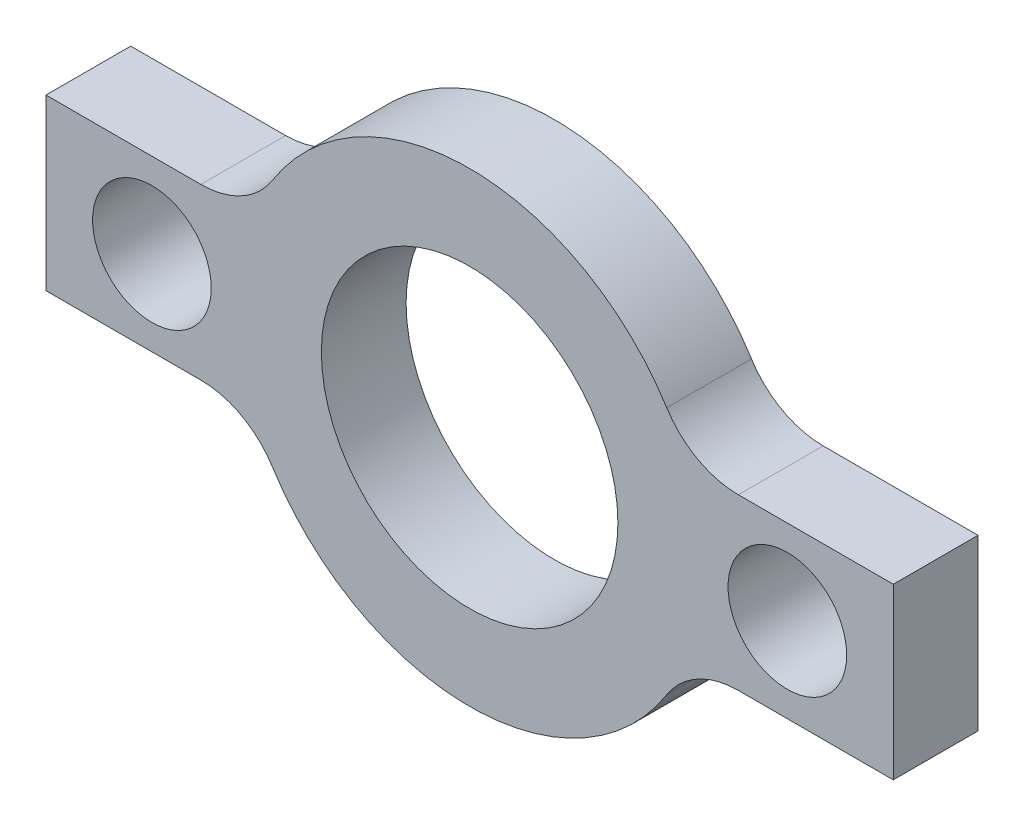
SolidWorks part; units mm, degrees
material "尼龙 101"
ref_plane "前视基准面" through (0, 0, 0) normal (0, 0, 1) x (1, 0, 0)
ref_plane "上视基准面" through (0, 0, 0) normal (0, 1, 0) x (1, 0, 0)
ref_plane "右视基准面" through (0, 0, 0) normal (1, 0, 0) x (0, 0, -1)
sketch "草图1" plane through (0, 0, 0) normal (0, 0, 1) x (1, 0, 0)
  line L0 (-10, 0) -> (10, 0) construction
  line L1 (-10, -2) -> (-6.3443, -2)
  line L2 (-10, 2) -> (-6.3443, 2)
  line L3 (-10, 2) -> (-10, -2)
  line L4 (10, 2) -> (10, -2)
  line L5 (6.3443, 2) -> (10, 2)
  line L6 (-10, 2) -> (10, 2) construction
  line L7 (6.3443, -2) -> (10, -2)
  line L8 (-10, -2) -> (10, -2) construction
  circle A0 centre (0, 0) radius 3.5
  arc A1 (4.6525, 2.9333) -> (-4.6525, 2.9333) centre (0, 0) ccw
  arc A2 (-4.6525, -2.9333) -> (4.6525, -2.9333) centre (0, 0) ccw
  arc A3 (4.6525, 2.9333) -> (6.3443, 2) centre (6.3443, 4) ccw
  arc A4 (6.3443, -2) -> (4.6525, -2.9333) centre (6.3443, -4) ccw
  arc A5 (-6.3443, -2) -> (-4.6525, -2.9333) centre (-6.3443, -4) cw
  arc A6 (-6.3443, 2) -> (-4.6525, 2.9333) centre (-6.3443, 4) ccw
  circle A7 centre (-7.5, 0) radius 1.4
  circle A8 centre (7.5, 0) radius 1.4
  point P19 (-5.1235, -2)
  dimension "D1" = 7
  dimension "D2" = 11
  dimension "D6" = 2
  dimension "D7" = 2.8
  dimension "D8" = 2.8
  dimension "D9" = 2.5
  dimension "D10" = 2.5
  dimension "D3" = 20
  dimension "D4" = 2
  dimension "D5" = 2
extrude "凸台-拉伸1" add sketch "草图1" along normal blind 2
